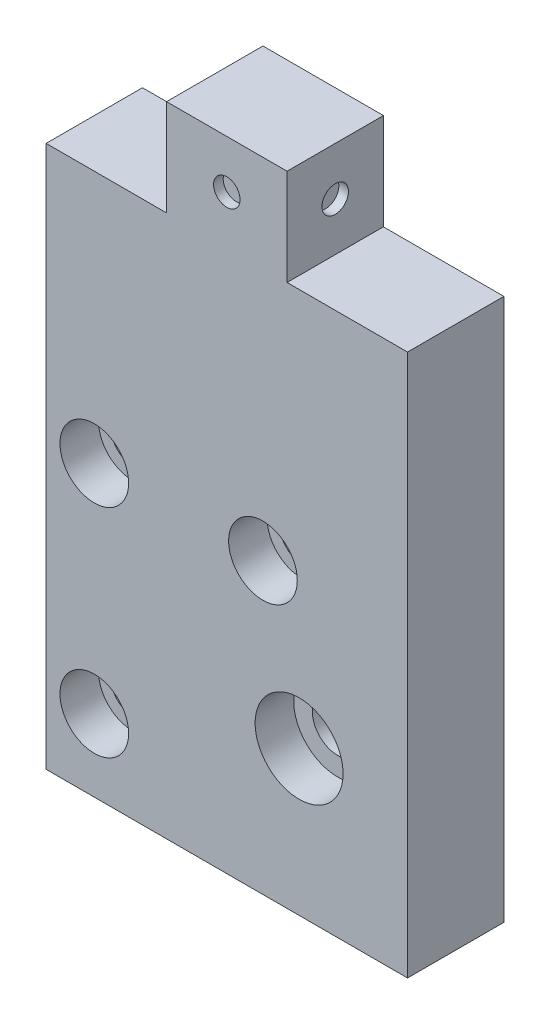
SolidWorks part; units mm, degrees
ref_plane "Front Plane" through (0, 0, 0) normal (0, 0, 1) x (1, 0, 0)
ref_plane "Top Plane" through (0, 0, 0) normal (0, 1, 0) x (1, 0, 0)
ref_plane "Right Plane" through (0, 0, 0) normal (1, 0, 0) x (0, 0, -1)
sketch "Sketch1" plane through (0, 0, 0) normal (0, 0, 1) x (1, 0, 0)
  line L0 (0, 57.15) -> (12.7, 57.15)
  line L1 (0, 0) -> (38.1, 0)
  line L5 (12.7, 57.15) -> (12.7, 67.31)
  line L6 (12.7, 67.31) -> (25.4, 67.31)
  line L7 (25.4, 67.31) -> (25.4, 57.15)
  line L8 (25.4, 57.15) -> (38.1, 57.15)
  line L9 (0, 57.15) -> (0, 0)
  line L10 (38.1, 57.15) -> (38.1, 0)
  line L11 (0, 74.3071) -> (10.16, 74.3071) construction
  line L12 (10.16, 74.3071) -> (10.16, 25.4) construction
  circle A0 centre (5.08, 7.62) radius 2.286
  circle A1 centre (5.08, 30.48) radius 2.286
  circle A2 centre (26.67, 15.24) radius 2.667
  circle A3 centre (22.86, 30.48) radius 2.286
  point P11 (29.337, 15.24)
  point P12 (24.003, 15.24)
  dimension "D3" = 7.62
  dimension "D5" = 4.572
  dimension "D6" = 4.572
  dimension "D8" = 29.337
  dimension "D9" = 12.7
  dimension "D10" = 10.16
  dimension "D13" = 17.78
  dimension "D14" = 4.572
  dimension "D16" = 15.24
  dimension "D1" = 38.1
  dimension "D2" = 5.08
  dimension "D4" = 24.003
  dimension "D7" = 22.86
  dimension "D11" = 10.16
  dimension "D12" = 25.4
  dimension "D15" = 5.08
  dimension "D17" = 57.15
extrude "Boss-Extrude1" add sketch "Sketch1" along normal blind 10.16
sketch "Sketch3" plane through (0, 0, 10.16) normal (0, 0, -1) x (-1, 0, 0)
  line L0 (-19.05, 67.31) -> (-19.05, 62.23) construction
  line L1 (-25.4, 67.31) -> (-12.7, 67.31) construction
  line L2 (-19.05, 62.23) -> (-12.7, 62.23) construction
  line L3 (-12.7, 67.31) -> (-12.7, 57.15) construction
  circle A0 centre (-19.05, 62.23) radius 1.397
  dimension "D1" = 2.794
sketch "Sketch7" plane through (0, 0, 10.16) normal (0, 0, 1) x (1, 0, 0)
  circle A0 centre (5.08, 30.48) radius 3.6195
  circle A1 centre (22.86, 30.48) radius 3.6195
  circle A2 centre (5.08, 7.62) radius 3.6195
  circle A3 centre (26.67, 15.24) radius 4.6355
  point P0 (5.08, 30.48)
  point P1 (5.08, 7.62)
  point P3 (22.86, 30.48)
  point P12 (26.67, 15.24)
  dimension "D1" = 7.239
  dimension "D2" = 7.239
  dimension "D3" = 7.239
  dimension "D4" = 9.271
extrude "Cut-Extrude1" cut sketch "Sketch7" against normal blind 4.064
extrude "Cut-Extrude2" cut sketch "Sketch3" along normal blind 1.016
sketch "Sketch8" plane through (25.4, 0, 0) normal (1, 0, 0) x (0, 0, -1)
  line L0 (-5.08, 62.23) -> (0, 62.23) construction
  line L1 (0, 57.15) -> (0, 67.31) construction
  line L2 (-5.08, 67.31) -> (-5.08, 62.23) construction
  line L3 (-10.16, 67.31) -> (0, 67.31) construction
  circle A0 centre (-5.08, 62.23) radius 1.397
  dimension "D1" = 2.794
extrude "Cut-Extrude3" cut sketch "Sketch8" against normal blind 1.016
sketch "Sketch9" plane through (12.7, 0, 0) normal (-1, 0, 0) x (0, 0, 1)
  line L0 (5.08, 62.23) -> (5.08, 67.31) construction
  line L1 (10.16, 67.31) -> (0, 67.31) construction
  line L2 (5.08, 62.23) -> (10.16, 62.23) construction
  line L3 (10.16, 67.31) -> (10.16, 57.15) construction
  circle A0 centre (5.08, 62.23) radius 1.397
  dimension "D1" = 2.794
extrude "Cut-Extrude4" cut sketch "Sketch9" against normal blind 1.016
